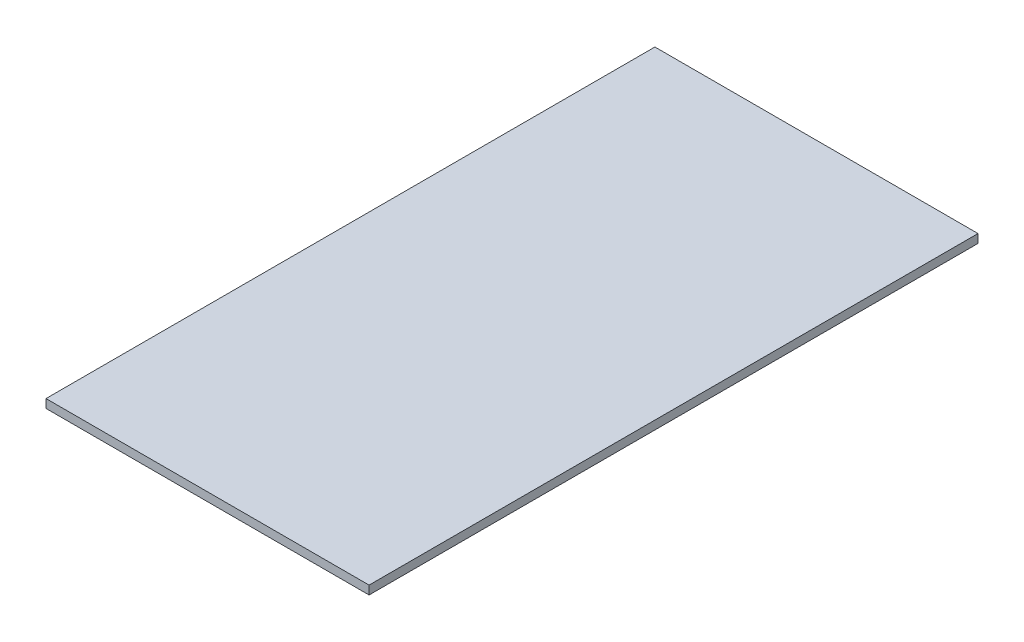
SolidWorks part; units mm, degrees
ref_plane "Front Plane" through (0, 0, 0) normal (0, 0, 1) x (1, 0, 0)
ref_plane "Top Plane" through (0, 0, 0) normal (0, 1, 0) x (1, 0, 0)
ref_plane "Right Plane" through (0, 0, 0) normal (1, 0, 0) x (0, 0, -1)
sketch "Sketch1" plane through (0, 0, 0) normal (0, 1, 0) x (1, 0, 0)
  line L1 (-112.75, -212.5) -> (112.75, -212.5)
  line L2 (-112.75, -212.5) -> (-112.75, 212.5)
  line L3 (-112.75, 212.5) -> (112.75, 212.5)
  line L4 (112.75, -212.5) -> (112.75, 212.5)
  line L5 (-112.75, -212.5) -> (112.75, 212.5) construction
  line L6 (-112.75, 212.5) -> (112.75, -212.5) construction
  point P0 (0, 0)
  dimension "D1" = 425
  dimension "D2" = 225.5
extrude "Boss-Extrude1" add sketch "Sketch1" along normal blind 6
